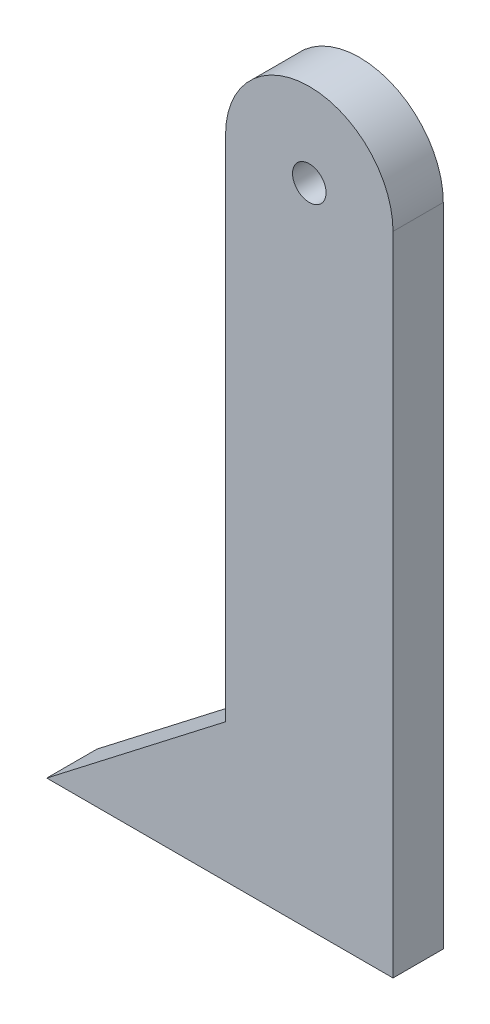
SolidWorks part; units mm, degrees
ref_plane "前视基准面" through (0, 0, 0) normal (0, 0, 1) x (1, 0, 0)
ref_plane "上视基准面" through (0, 0, 0) normal (0, 1, 0) x (1, 0, 0)
ref_plane "右视基准面" through (0, 0, 0) normal (1, 0, 0) x (0, 0, -1)
sketch "草图1" plane through (0, 0, 0) normal (0, 0, 1) x (1, 0, 0)
  line L0 (-5, 0) -> (-5, -30.3571)
  line L1 (-5, -30.3571) -> (5, -30.3571)
  line L2 (5, -30.3571) -> (5, 0)
  arc A0 (5, 0) -> (-5, 0) centre (0, 0) ccw
  circle A1 centre (0, 0) radius 1
  dimension "D1" = 10
  dimension "D2" = 2
extrude "凸台-拉伸1" add sketch "草图1" along normal blind 3
sketch "草图2" plane through (0, 0, 3) normal (0, 0, 1) x (1, 0, 0)
  line L0 (-5, -30.3571) -> (5, -30.3571)
  line L1 (5, -35.669) -> (5.7209, -35.669)
  line L2 (-5, -30.3571) -> (-15.6781, -38.6069)
  line L3 (-15.6781, -38.6069) -> (5, -38.6069)
  line L4 (5, -30.3571) -> (5, -35.669)
  line L5 (5, -38.6069) -> (5, -35.669)
  line M3 (-5, -30.3571) -> (5, -30.3571)
extrude "凸台-拉伸2" add sketch "草图2" against normal up to surface (3 mm away) contours L3 L5 L4 L2 M3 up to face at (0, -13.9286, 0)
